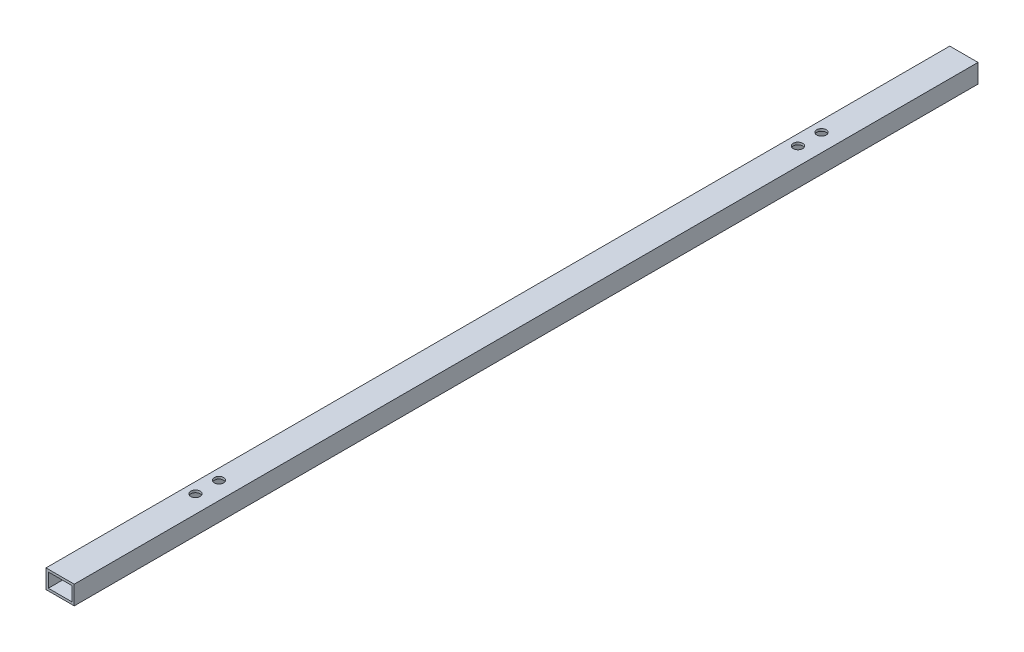
SolidWorks part; units mm, degrees
material "6061 Alloy"
ref_plane "Front Plane" through (0, 0, 0) normal (0, 0, 1) x (1, 0, 0)
ref_plane "Top Plane" through (0, 0, 0) normal (0, 1, 0) x (1, 0, 0)
ref_plane "Right Plane" through (0, 0, 0) normal (1, 0, 0) x (0, 0, -1)
sketch "Sketch1" plane through (0, 0, 0) normal (0, 0, 1) x (1, 0, 0)
  line L0 (19.05, 0) -> (15.875, 0) construction
  line L1 (-19.05, 0) -> (19.05, 0) construction
  line L2 (0, 12.7) -> (0, -12.7)
  point P7 (0, 0)
sketch "Sketch2" plane through (0, 0, 0) normal (1, 0, 0) x (0, 0, -1)
  line L0 (609.6, 0) -> (-609.6, 0)
  point P4 (0, 0)
  dimension "Length" = 1219.2
sketch "Sketch3" plane through (0, 0, 0) normal (0, 0, 1) x (1, 0, 0)
  line L0 (-19.05, 0) -> (19.05, 0) construction
  line L5 (19.05, -12.7) -> (-19.05, -12.7)
  line L6 (19.05, -12.7) -> (19.05, 12.7)
  line L11 (19.05, 12.7) -> (-19.05, 12.7)
  line L12 (-19.05, -12.7) -> (-19.05, 12.7)
  line L14 (19.05, -12.7) -> (-19.05, 12.7) construction
  line L15 (19.05, 12.7) -> (-19.05, -12.7) construction
  line L16 (15.875, -9.525) -> (-15.875, -9.525)
  line L17 (15.875, -9.525) -> (15.875, 9.525)
  line L18 (15.875, 9.525) -> (-15.875, 9.525)
  line L19 (-15.875, -9.525) -> (-15.875, 9.525)
  line L20 (15.875, -9.525) -> (-15.875, 9.525) construction
  line L21 (15.875, 9.525) -> (-15.875, -9.525) construction
  point P0 (0, 0)
  point P5 (0, 0)
  point P13 (15.875, -12.7)
  dimension "D1" = 3.175
  dimension "D3" = 38.1
  dimension "D4" = 25.4
  dimension "D2" = 3.175
extrude "Boss-Extrude1" add sketch "Sketch3" along normal up to vertex (609.6 mm away) and the other way up to vertex (609.6 mm away) up to point (0, 0, 609.6) other way up to point (0, 0, -609.6)
sketch "Sketch5" plane through (0, 0, 0) normal (1, 0, 0) x (0, 0, -1)
  line L0 (-609.6, 0) -> (609.6, 0) construction
  line L3 (-609.6, -12.7) -> (-609.6, 12.7) construction
  line L4 (609.6, -12.7) -> (609.6, 12.7) construction
  point P6 (-566.7375, 0)
  point P7 (-552.45, 0)
  point P8 (552.45, 0)
  point P10 (566.7375, 0)
  dimension "D1" = 42.8625
  dimension "D2" = 57.15
  dimension "D3" = 42.8625
  dimension "D4" = 57.15
sketch "Sketch6" plane through (0, 12.7, 0) normal (0, 1, 0) x (1, 0, 0)
  line L0 (19.05, 609.6) -> (-19.05, 609.6) construction
  line L1 (-19.05, 0) -> (19.05, 0) construction
  line L2 (-19.05, -609.6) -> (-19.05, 609.6) construction
  line L3 (19.05, -609.6) -> (19.05, 609.6) construction
  line L4 (-15.875, -609.6) -> (-15.875, 609.6)
  line L5 (-15.875, -609.6) -> (-15.875, 609.6)
  line L6 (-15.875, 406.4) -> (6.35, 406.4) construction
  line L7 (6.35, -609.6) -> (6.35, 609.6)
  line L8 (6.35, -609.6) -> (6.35, 609.6)
  line L9 (-4.7625, 406.4) -> (-4.7625, 438.15) construction
  circle A0 centre (-4.7625, 422.275) radius 6.35
  circle A1 centre (-4.7625, 390.525) radius 6.35
  circle A2 centre (-4.7625, -422.275) radius 6.35
  circle A3 centre (-4.7625, -390.525) radius 6.35
  dimension "D1" = 203.2
  dimension "D4" = 31.75
  dimension "D2" = 3.175
  dimension "D3" = 12.7
extrude "Cut-Extrude1" cut sketch "Sketch6" against normal through all contours A3 | A2 | A0 | A1
equation "\"D1@Sketch3\"=\"Wall thickness@Sketch1\""
equation "\"D1@Sketch5\"=\"Width@Sketch1\"*1.125"
equation "\"D2@Sketch5\"=\"Width@Sketch1\"*1.5"
equation "\"D3@Sketch5\"=\"D1@Sketch5\""
equation "\"D4@Sketch5\"=\"D2@Sketch5\""
equation "\"D2@Sketch3\"=\"Wall Thickness@Sketch1\""
